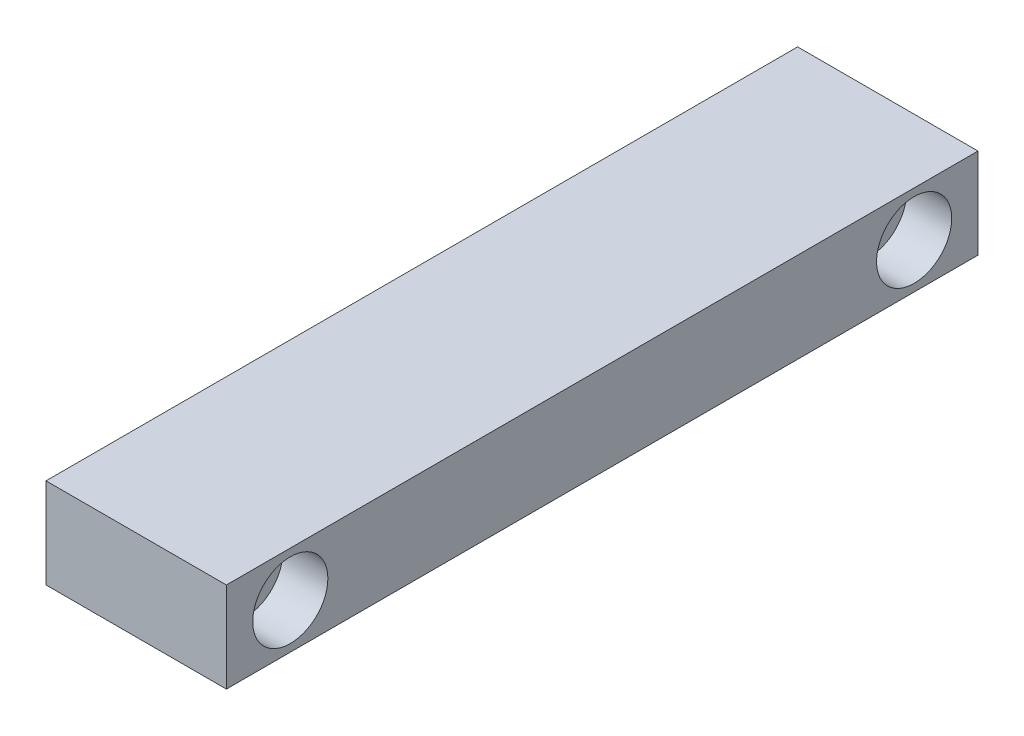
SolidWorks part; units mm, degrees
material "Sapin"
ref_plane "Plan de face" through (0, 0, 0) normal (0, 0, 1) x (1, 0, 0)
ref_plane "Plan de dessus" through (0, 0, 0) normal (0, 1, 0) x (1, 0, 0)
ref_plane "Plan de droite" through (0, 0, 0) normal (1, 0, 0) x (0, 0, -1)
sketch "Esquisse1" plane through (0, 0, 0) normal (0, 1, 0) x (1, 0, 0)
  line L1 (-24, -100) -> (24, -100)
  line L2 (-24, -100) -> (-24, 100)
  line L3 (-24, 100) -> (24, 100)
  line L4 (24, -100) -> (24, 100)
  line L5 (-24, -100) -> (24, 100) construction
  line L6 (-24, 100) -> (24, -100) construction
  point P0 (0, 0)
  dimension "D1" = 200
  dimension "D2" = 48
extrude "Boss.-Extru.1" add sketch "Esquisse1" along normal blind 24
sketch "Esquisse2" plane through (24, 0, 0) normal (1, 0, 0) x (0, 0, -1)
  line L0 (0, 0) -> (0, 61.5655) construction
  line L1 (100, 24) -> (100, 0) construction
  line L2 (-100, 0) -> (100, 0) construction
  circle A0 centre (-83, 12) radius 4
  circle A2 centre (83, 12) radius 4
  dimension "D4" = 8
  dimension "D2" = 17
  dimension "D3" = 12
extrude "Enlèv. mat.-Extru.1" cut sketch "Esquisse2" against normal through all
sketch "Esquisse3" plane through (24, 0, 0) normal (1, 0, 0) x (0, 0, -1)
  circle A0 centre (-83, 12) radius 10
  circle A2 centre (83, 12) radius 10
  dimension "D1" = 20
extrude "Enlèv. mat.-Extru.2" cut sketch "Esquisse3" against normal blind 12
sketch "Esquisse4" plane through (-24, 0, 0) normal (-1, 0, 0) x (0, 0, 1)
  circle A0 centre (-83, 12) radius 7
  circle A2 centre (83, 12) radius 7
  dimension "D1" = 14
extrude "Enlèv. mat.-Extru.3" cut sketch "Esquisse4" against normal blind 12
